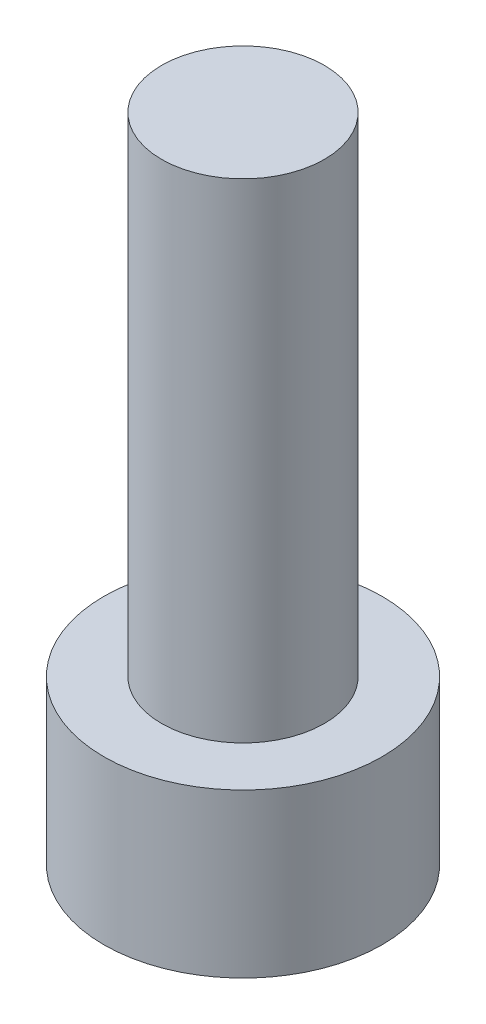
SolidWorks part; units mm, degrees
ref_plane "Front Plane" through (0, 0, 0) normal (0, 0, 1) x (1, 0, 0)
ref_plane "Top Plane" through (0, 0, 0) normal (0, 1, 0) x (1, 0, 0)
ref_plane "Right Plane" through (0, 0, 0) normal (1, 0, 0) x (0, 0, -1)
sketch "Sketch1" plane through (0, 0, 0) normal (0, 1, 0) x (1, 0, 0)
  circle A0 centre (0, 0) radius 3.415
  dimension "D1" = 6.83
extrude "Boss-Extrude1" add sketch "Sketch1" along normal blind 4
sketch "Sketch2" plane through (0, 4, 0) normal (0, 1, 0) x (1, 0, 0)
  circle A0 centre (0, 0) radius 2
  dimension "D1" = 4
extrude "Boss-Extrude2" add sketch "Sketch2" along normal blind 12
